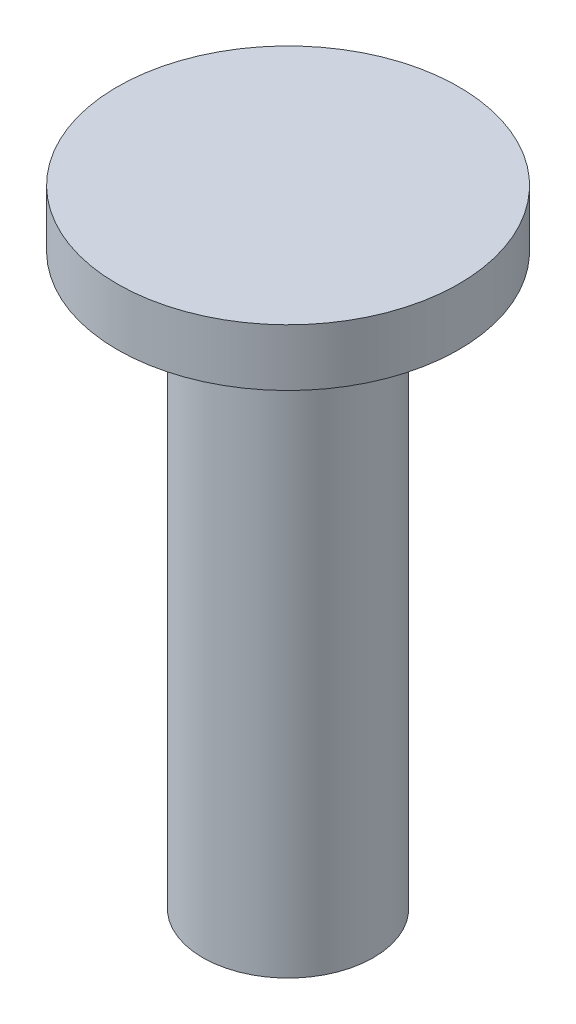
SolidWorks part; units mm, degrees
ref_plane "Front Plane" through (0, 0, 0) normal (0, 0, 1) x (1, 0, 0)
ref_plane "Top Plane" through (0, 0, 0) normal (0, 1, 0) x (1, 0, 0)
ref_plane "Right Plane" through (0, 0, 0) normal (1, 0, 0) x (0, 0, -1)
sketch "Sketch1" plane through (0, 0, 0) normal (0, 1, 0) x (1, 0, 0)
  circle A0 centre (0, 0) radius 9.525
  dimension "D1" = 19.05
extrude "Boss-Extrude1" add sketch "Sketch1" along normal blind 63.5
sketch "Sketch2" plane through (0, 63.5, 0) normal (0, 1, 0) x (1, 0, 0)
  circle A0 centre (0, 0) radius 19.05
  dimension "D1" = 38.1
extrude "Boss-Extrude2" add sketch "Sketch2" along normal blind 6.35
